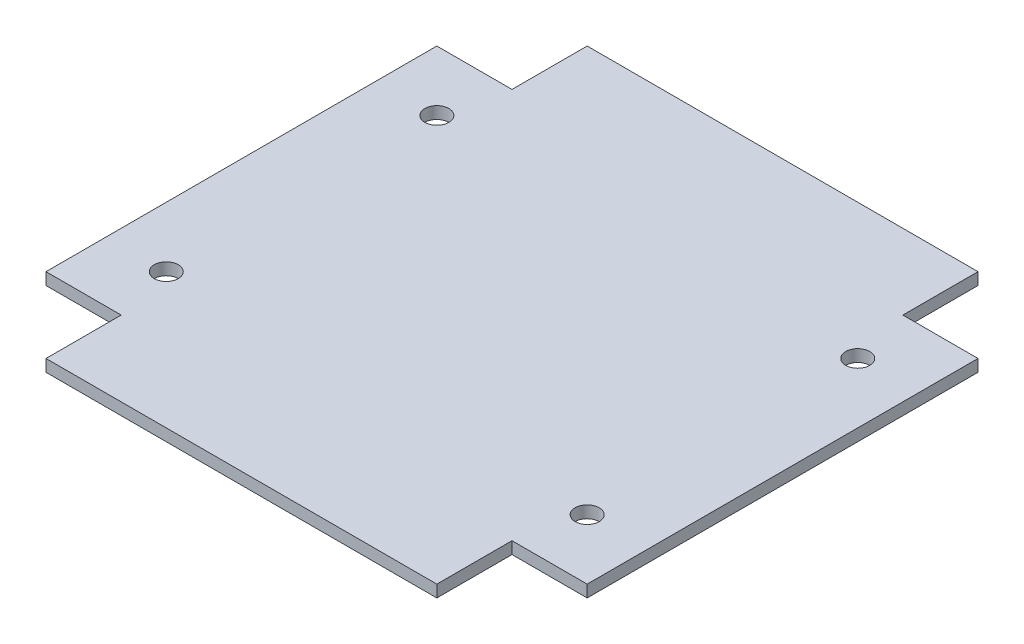
SolidWorks part; units mm, degrees
ref_plane "Front Plane" through (0, 0, 0) normal (0, 0, 1) x (1, 0, 0)
ref_plane "Top Plane" through (0, 0, 0) normal (0, 1, 0) x (1, 0, 0)
ref_plane "Right Plane" through (0, 0, 0) normal (1, 0, 0) x (0, 0, -1)
sketch "Sketch1" plane through (0, 0, 0) normal (0, 1, 0) x (1, 0, 0)
  line L0 (-53.9706, 35.1103) -> (-41.4706, 35.1103)
  line L1 (-41.4706, 35.1103) -> (-41.4706, 47.6103)
  line L2 (-41.4706, 47.6103) -> (23.5294, 47.6103)
  line L3 (23.5294, 47.6103) -> (23.5294, 35.1103)
  line L4 (23.5294, 35.1103) -> (36.0294, 35.1103)
  line L5 (36.0294, 35.1103) -> (36.0294, -29.8897)
  line L6 (36.0294, -29.8897) -> (23.5294, -29.8897)
  line L7 (23.5294, -29.8897) -> (23.5294, -42.3897)
  line L8 (23.5294, -42.3897) -> (-41.4706, -42.3897)
  line L9 (-41.4706, -42.3897) -> (-41.4706, -29.8897)
  line L10 (-41.4706, -29.8897) -> (-53.9706, -29.8897)
  line L11 (-53.9706, -29.8897) -> (-53.9706, 35.1103)
  point P10 (0, 0)
  dimension "D1" = 90
  dimension "D2" = 90
  dimension "D3" = 12.5
  dimension "D4" = 12.5
  dimension "D5" = 12.5
  dimension "D6" = 12.5
  dimension "D7" = 12.5
  dimension "D8" = 12.5
  dimension "D9" = 12.5
  dimension "D10" = 12.5
extrude "Boss-Extrude1" add sketch "Sketch1" along normal blind 2
sketch "Sketch2" plane through (0, 2, 0) normal (0, 1, 0) x (1, 0, 0)
  line L0 (-53.9706, 25.1103) -> (36.0294, 25.1103) construction
  line L1 (-53.9706, 35.1103) -> (-53.9706, -29.8897) construction
  line L2 (36.0294, -29.8897) -> (36.0294, 35.1103) construction
  line L3 (-53.9706, -19.8897) -> (36.0294, -19.8897) construction
  line L4 (-43.9706, 47.6103) -> (-43.9706, -42.3897) construction
  line L5 (23.5294, 47.6103) -> (-41.4706, 47.6103) construction
  line L6 (-41.4706, -42.3897) -> (23.5294, -42.3897) construction
  line L7 (26.0294, 47.6103) -> (26.0294, -42.3897) construction
  point P16 (-43.9706, 25.1103)
  point P17 (-43.9706, -19.8897)
  point P18 (26.0294, -19.8897)
  point P19 (26.0294, 25.1103)
  dimension "D1" = 45
  dimension "D2" = 22.5
  dimension "D3" = 10
  dimension "D4" = 70
hole_wizard "Ø4.0mm Dowel Hole1" positions "Sketch5" profile "Sketch6" hole size "Ø4.0" standard "ISO" end condition through all
sketch "Sketch5" plane through (0, 2, 0) normal (0, 1, 0) x (1, 0, 0)
  point P0 (-43.9706, 25.1103)
  point P3 (26.0294, 25.1103)
  point P6 (-43.9706, -19.8897)
  point P9 (26.0294, -19.8897)
sketch "Sketch6" plane through (-43.9706, 2, -25.1103) normal (1, 0, 0) x (0, 0, 1)
  line L0 (0, 0) -> (0, 2)
  line L1 (0, 2) -> (2, 2)
  line L2 (2, 2) -> (2, 0)
  line L5 (2, 0) -> (0, 0)
  line L11 (0, -6.35) -> (0, 107.95) construction
  dimension "Thru Hole Dia." = 4
  dimension "Thru Hole Depth" = 2
